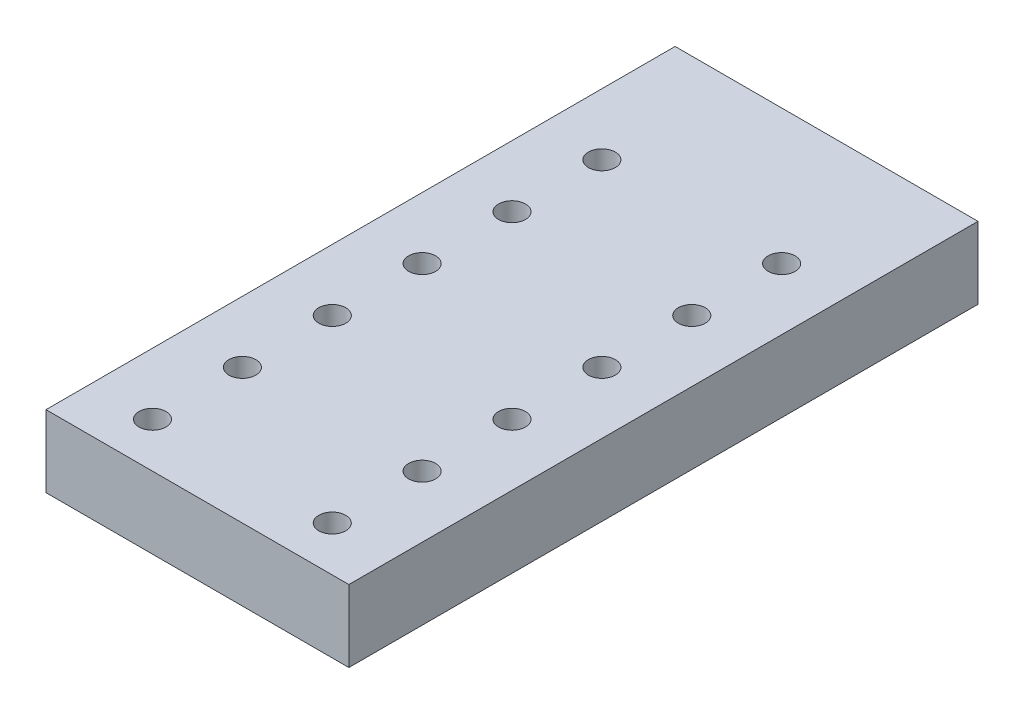
SolidWorks part; units mm, degrees
ref_plane "前视基准面" through (0, 0, 0) normal (0, 0, 1) x (1, 0, 0)
ref_plane "上视基准面" through (0, 0, 0) normal (0, 1, 0) x (1, 0, 0)
ref_plane "右视基准面" through (0, 0, 0) normal (1, 0, 0) x (0, 0, -1)
sketch "草图1" plane through (0, 0, 0) normal (0, 0, 1) x (1, 0, 0)
  line L1 (-16.85, -4) -> (16.85, -4)
  line L2 (-16.85, -4) -> (-16.85, 4)
  line L3 (-16.85, 4) -> (16.85, 4)
  line L4 (16.85, -4) -> (16.85, 4)
  line L5 (-16.85, -4) -> (16.85, 4) construction
  line L6 (-16.85, 4) -> (16.85, -4) construction
  point P0 (0, 0)
  dimension "D1" = 33.7
  dimension "D2" = 8
extrude "凸台-拉伸1" add sketch "草图1" along normal blind 70
sketch "草图2" plane through (0, 0, 0) normal (0, 0, -1) x (-1, 0, 0)
  circle A0 centre (10, 0) radius 2.5
  circle A1 centre (-10, 0) radius 2.5
  dimension "D1" = 10
  dimension "D3" = 5
  dimension "D4" = 5
  dimension "D2" = 10
extrude "切除-拉伸1" cut sketch "草图2" against normal blind 10
sketch "草图3" plane through (0, -4, 0) normal (0, -1, 0) x (1, 0, 0)
  line L0 (-16.85, 0) -> (16.85, 0) construction
  circle A0 centre (-10, 15) radius 2.5
  circle A1 centre (10, 15) radius 2.5
  point P6 (0, 0)
  dimension "D1" = 5
  dimension "D2" = 5
  dimension "D3" = 10
  dimension "D4" = 20
  dimension "D5" = 15
  dimension "D6" = 15
extrude "切除-拉伸2" cut sketch "草图3" against normal blind 4
sketch "草图4" plane through (0, 0, 0) normal (0, -1, 0) x (-1, 0, 0)
  circle A0 centre (10, -15) radius 1.5
  circle A1 centre (-10, -15) radius 1.5
  dimension "D1" = 3
  dimension "D2" = 3
extrude "切除-拉伸3" cut sketch "草图4" against normal blind 4
pattern_linear "阵列(线性)1" count 6 spacing 10 along (0, 0, 1) of "切除-拉伸3", "切除-拉伸2"
